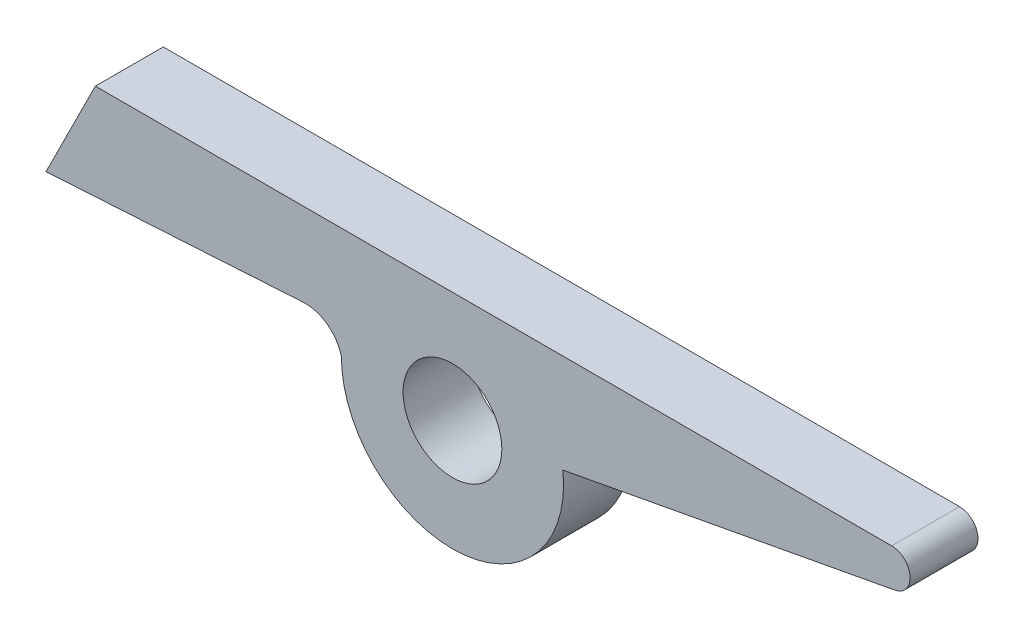
SolidWorks part; units mm, degrees
ref_plane "Front Plane" through (0, 0, 0) normal (0, 0, 1) x (1, 0, 0)
ref_plane "Top Plane" through (0, 0, 0) normal (0, 1, 0) x (1, 0, 0)
ref_plane "Right Plane" through (0, 0, 0) normal (1, 0, 0) x (0, 0, -1)
sketch "Sketch3" plane through (0, 0, 0) normal (0, 0, 1) x (1, 0, 0)
  line L0 (0, 0) -> (8.94, 0) construction
  line L1 (-28.9273, 9) -> (35.5727, 9)
  line L2 (-28.9273, 9) -> (-32.9273, 9) construction
  line L3 (-32.9273, 9) -> (-32.9273, 1) construction
  line L4 (-28.9273, 9) -> (-32.9273, 1)
  line L5 (0, 0) -> (-9, 0) construction
  line L6 (-32.9273, 1) -> (-12.0876, 2.2546)
  line L7 (35.8481, 6.0255) -> (8.94, 1)
  circle A0 centre (0, 0) radius 4
  arc A1 (-9, 0) -> (8.9442, 1.0008) centre (0, 0) ccw
  arc A2 (-12.0876, 2.2546) -> (-9, 0) centre (-11.9073, -0.74) cw
  arc A3 (35.5727, 9) -> (35.8481, 6.0255) centre (35.5727, 7.5) cw
  point P13 (0, 0)
  point P15 (35.8742, 6.0306)
  point P17 (0, 0)
  point P18 (-9, 0)
  point P19 (0, 0)
  point P20 (-19.3454, 0.8111)
  point P21 (35.2318, 6.0261)
  point P22 (0, 0)
  dimension "D1" = 8
  dimension "D2" = 18
  dimension "D8" = 1.74
  dimension "D10" = 3
  dimension "D11" = 1.5
  dimension "D3" = 8.94
  dimension "D4" = 64.5
  dimension "D5" = 9
  dimension "D6" = 4
  dimension "D7" = 8
  dimension "D9" = 21.02
  dimension "D12" = 8
extrude "Boss-Extrude1" add sketch "Sketch3" along normal blind 5.5
